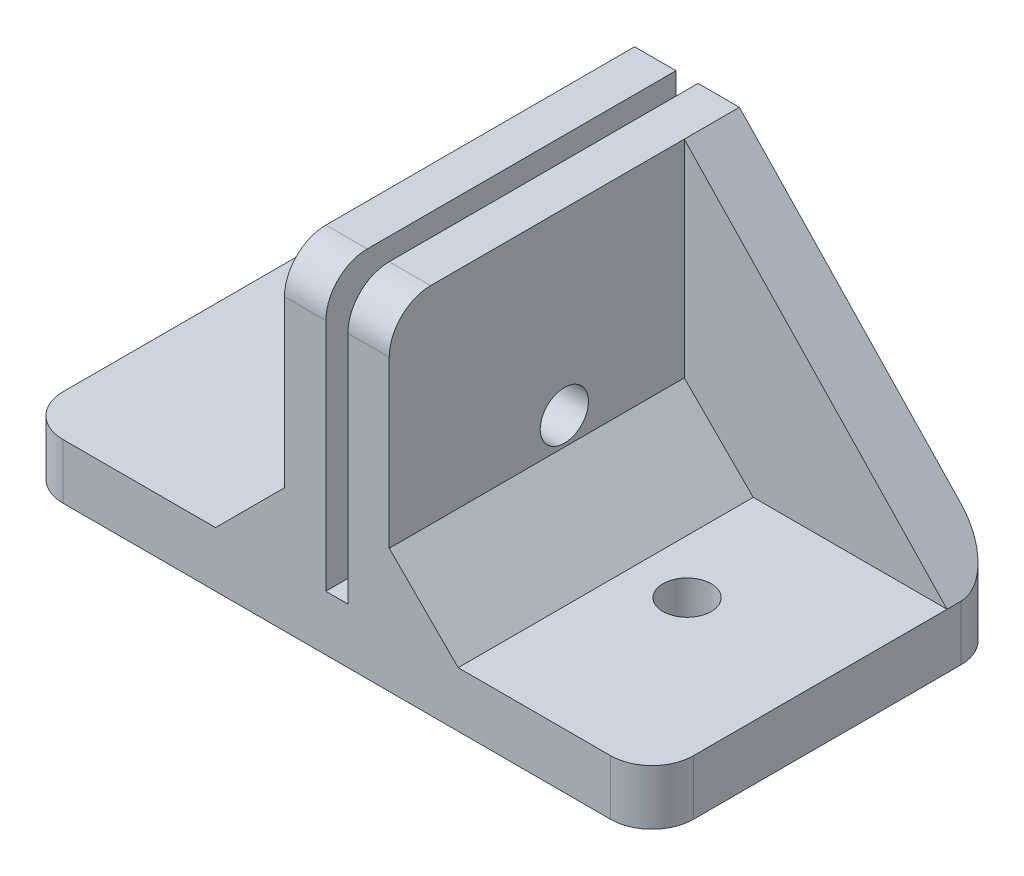
SolidWorks part; units mm, degrees
ref_plane "Front Plane" through (0, 0, 0) normal (0, 0, 1) x (1, 0, 0)
ref_plane "Top Plane" through (0, 0, 0) normal (0, 1, 0) x (1, 0, 0)
ref_plane "Right Plane" through (0, 0, 0) normal (1, 0, 0) x (0, 0, -1)
sketch "Sketch1" plane through (0, 0, 0) normal (0, 1, 0) x (1, 0, 0)
  line L1 (-22.86, 12.7) -> (22.86, 12.7)
  line L2 (-22.86, 12.7) -> (-22.86, -12.7)
  line L3 (-22.86, -12.7) -> (22.86, -12.7)
  line L4 (22.86, 12.7) -> (22.86, -12.7)
  line L5 (-22.86, 12.7) -> (22.86, -12.7) construction
  line L6 (-22.86, -12.7) -> (22.86, 12.7) construction
  point P0 (0, 0)
  dimension "D1" = 25.4
  dimension "D2" = 45.72
extrude "Boss-Extrude1" add sketch "Sketch1" along normal blind 4
sketch "Sketch2" plane through (0, 4, 0) normal (0, 1, 0) x (1, 0, 0)
  line L0 (22.86, 12.7) -> (-22.86, 12.7) construction
  line L1 (-3.8, 12.7) -> (-0.8, 12.7)
  line L2 (-3.8, 12.7) -> (-3.8, -12.7)
  line L3 (-3.8, -12.7) -> (-0.8, -12.7)
  line L4 (-0.8, 12.7) -> (-0.8, -12.7)
  line L5 (-22.86, -12.7) -> (22.86, -12.7) construction
  line L6 (22.86, -12.7) -> (22.86, 12.7) construction
  line L7 (0.8, 12.7) -> (3.8, 12.7)
  line L8 (0.8, 12.7) -> (0.8, -12.7)
  line L9 (0.8, -12.7) -> (3.8, -12.7)
  line L10 (3.8, 12.7) -> (3.8, -12.7)
  dimension "D1" = 1.6
  dimension "D2" = 3
  dimension "D3" = 3
  dimension "D4" = 22.06
extrude "Boss-Extrude2" add sketch "Sketch2" along normal blind 20
chamfer "Chamfer1" distance 5 angle 45 2 edges at (3.8, 4, 0) (-3.8, 4, 0)
sketch "Sketch3" plane through (0, 0, -12.7) normal (0, 0, -1) x (-1, 0, 0)
  line L0 (-3.8, 24) -> (-22.86, 4)
  line L1 (-22.86, 4) -> (-3.8, 4)
  line L2 (-3.8, 4) -> (-3.8, 24)
  line L3 (3.8, 24) -> (3.8, 4)
  line L4 (3.8, 4) -> (22.86, 4)
  line L5 (22.86, 4) -> (3.8, 24)
extrude "Boss-Extrude3" add sketch "Sketch3" against normal blind 4
sketch "Sketch4" plane through (0, 0, 0) normal (0, -1, 0) x (1, 0, 0)
  line L0 (-22.86, -12.7) -> (-22.86, 12.7) construction
  circle A0 centre (-12.7, 0) radius 1.75
  circle A1 centre (12.7, 0) radius 1.75
  dimension "D1" = 3.5
  dimension "D2" = 3.5
  dimension "D3" = 25.4
  dimension "D4" = 10.16
extrude "Cut-Extrude1" cut sketch "Sketch4" against normal blind 4
sketch "Sketch5" plane through (-3.8, 0, 0) normal (-1, 0, 0) x (0, 0, 1)
  line L0 (-8.7, 24) -> (12.7, 24) construction
  line L1 (12.7, 24) -> (12.7, 9) construction
  circle A0 centre (0, 11) radius 1.75
  dimension "D1" = 3.5
  dimension "D2" = 13
  dimension "D3" = 12.7
extrude "Cut-Extrude2" cut sketch "Sketch5" against normal blind 14
fillet "Fillet1" radius 3 6 edges at (2.3, 24, 12.7) (-2.3, 24, 12.7) (22.86, 2, -12.7) (22.86, 2, 12.7) (-22.86, 2, -12.7) (-22.86, 2, 12.7)
